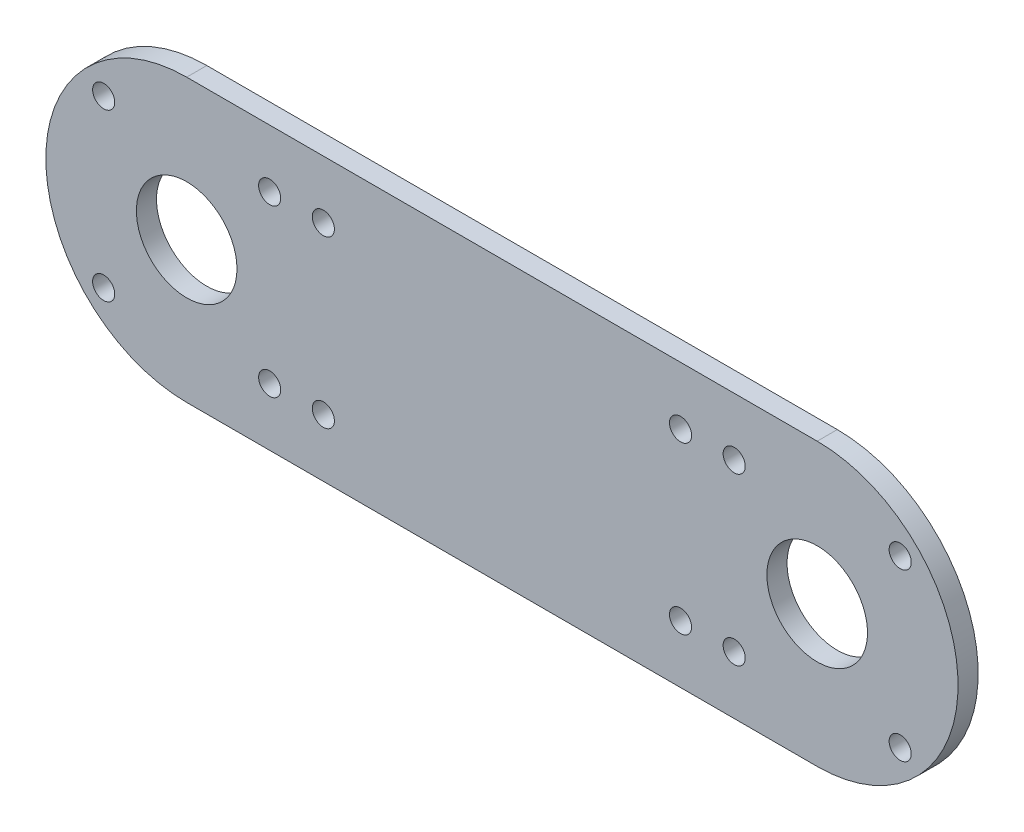
SolidWorks part; units mm, degrees
material "Thornel Mat VMA"
ref_plane "前视基准面" through (0, 0, 0) normal (0, 0, 1) x (1, 0, 0)
ref_plane "上视基准面" through (0, 0, 0) normal (0, 1, 0) x (1, 0, 0)
ref_plane "右视基准面" through (0, 0, 0) normal (1, 0, 0) x (0, 0, -1)
sketch "草图1" plane through (0, 0, 0) normal (0, 0, 1) x (1, 0, 0)
  line L0 (0, 0) -> (0, 46.6329) construction
  line L1 (75, -10) -> (-75, -10) construction
  line L2 (75, -10) -> (75, 10) construction
  line L3 (75, 10) -> (-75, 10) construction
  line L4 (-75, -10) -> (-75, 10) construction
  line L5 (75, -10) -> (-75, 10) construction
  line L6 (75, 10) -> (-75, -10) construction
  line L7 (82.5, -21) -> (-82.5, -21)
  line L8 (82.5, -21) -> (82.5, 21)
  line L9 (82.5, 21) -> (-82.5, 21)
  line L10 (-82.5, -21) -> (-82.5, 21)
  line L11 (82.5, -21) -> (-82.5, 21) construction
  line L12 (82.5, 21) -> (-82.5, -21) construction
  line L13 (-34.6256, -12.3744) -> (-59.3744, -12.3744) construction
  line L14 (-34.6256, -12.3744) -> (-34.6256, 12.3744) construction
  line L15 (-34.6256, 12.3744) -> (-59.3744, 12.3744) construction
  line L16 (-59.3744, -12.3744) -> (-59.3744, 12.3744) construction
  line L17 (-34.6256, -12.3744) -> (-59.3744, 12.3744) construction
  line L18 (-34.6256, 12.3744) -> (-59.3744, -12.3744) construction
  line L19 (59.3744, -12.3744) -> (59.3744, 12.3744) construction
  line L20 (34.6256, -12.3744) -> (34.6256, 12.3744) construction
  line L21 (34.6256, 12.3744) -> (59.3744, -12.3744) construction
  line L22 (34.6256, -12.3744) -> (59.3744, 12.3744) construction
  line L23 (34.6256, 12.3744) -> (59.3744, 12.3744) construction
  line L24 (34.6256, -12.3744) -> (59.3744, -12.3744) construction
  line L25 (-82.5, 21) -> (82.5, -21) construction
  line L26 (-82.5, -21) -> (82.5, 21) construction
  line L27 (-75, 10) -> (75, -10) construction
  line L28 (-75, -10) -> (75, 10) construction
  circle A0 centre (-47, 0) radius 7.5
  circle A1 centre (-75, 10) radius 1.65
  circle A2 centre (-75, -10) radius 1.65
  circle A3 centre (75, 10) radius 1.65
  circle A4 centre (75, -10) radius 1.65
  circle A5 centre (-59.3744, 12.3744) radius 1.65
  circle A6 centre (-34.6256, 12.3744) radius 1.65
  circle A7 centre (-34.6256, -12.3744) radius 1.65
  circle A8 centre (-59.3744, -12.3744) radius 1.65
  circle A9 centre (59.3744, -12.3744) radius 1.65
  circle A10 centre (34.6256, -12.3744) radius 1.65
  circle A11 centre (34.6256, 12.3744) radius 1.65
  circle A12 centre (59.3744, 12.3744) radius 1.65
  circle A13 centre (47, 0) radius 7.5
  point P0 (0, 0)
  point P5 (0, 0)
  dimension "D5" = 15
  dimension "D6" = 3.3
  dimension "D7" = 3.3
  dimension "D8" = 3.3
  dimension "D9" = 3.3
  dimension "D10" = 47
  dimension "D11" = 17.5
  dimension "D12" = 3.3
  dimension "D13" = 3.3
  dimension "D14" = 3.3
  dimension "D15" = 3.3
  dimension "D1" = 20
  dimension "D2" = 150
  dimension "D3" = 42
  dimension "D4" = 165
extrude "凸台-拉伸1" add sketch "草图1" along normal blind 3
sketch "草图2" plane through (0, 0, 3) normal (0, 0, 1) x (1, 0, 0)
  line L0 (-47, 21) -> (-82.5, 21)
  line L1 (-82.5, 21) -> (-82.5, -21)
  line L2 (-82.5, 21) -> (-82.5, -21) construction
  line L3 (-82.5, -21) -> (-47, -21)
  line L4 (47, -21) -> (82.5, -21)
  line L5 (82.5, -21) -> (82.5, 21)
  line L6 (82.5, 21) -> (47, 21)
  arc A0 (-47, 21) -> (-47, -21) centre (-47, 0) ccw
  arc A1 (47, -21) -> (47, 21) centre (47, 0) ccw
extrude "切除-拉伸1" cut sketch "草图2" against normal blind 3
sketch "草图3" plane through (0, 0, 3) normal (0, 0, 1) x (1, 0, 0)
  line L0 (-34.6256, 12.3744) -> (34.6256, 12.3744) construction
  line L1 (-34.6256, -12.3744) -> (34.6256, -12.3744) construction
  circle A0 centre (-26.6256, 12.3744) radius 1.65
  circle A1 centre (-26.6256, -12.3744) radius 1.65
  circle A2 centre (26.6256, 12.3744) radius 1.65
  circle A3 centre (26.6256, -12.3744) radius 1.65
  circle A4 centre (-34.6256, 12.3744) radius 1.65 construction
  circle A5 centre (-34.6256, -12.3744) radius 1.65 construction
  circle A6 centre (34.6256, 12.3744) radius 1.65 construction
  circle A7 centre (34.6256, -12.3744) radius 1.65 construction
  dimension "D1" = 3.3
  dimension "D2" = 3.3
  dimension "D3" = 3.3
  dimension "D4" = 3.3
  dimension "D5" = 8
  dimension "D6" = 8
  dimension "D7" = 8
  dimension "D8" = 8
extrude "切除-拉伸2" cut sketch "草图3" against normal blind 3
